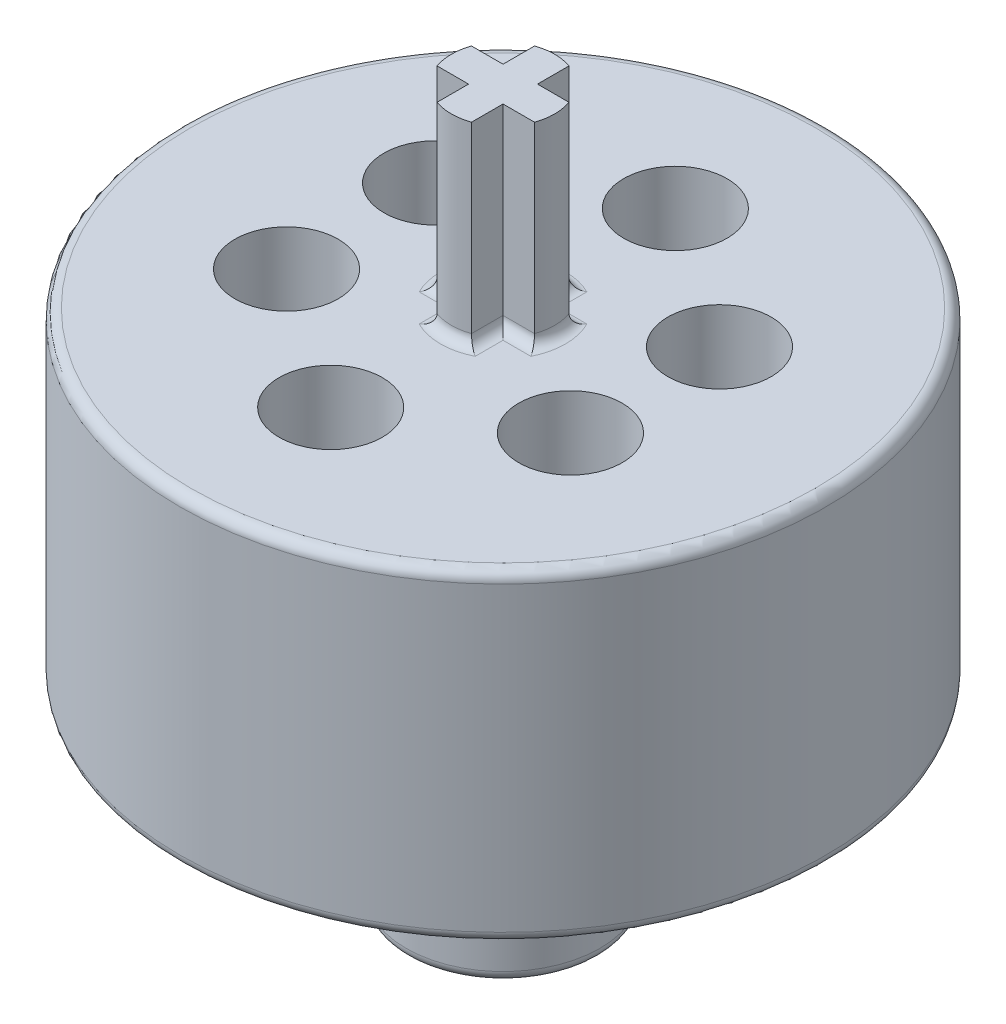
SolidWorks part; units mm, degrees
ref_plane "Plano frontal" through (0, 0, 0) normal (0, 0, 1) x (1, 0, 0)
ref_plane "Plano superior" through (0, 0, 0) normal (0, 1, 0) x (1, 0, 0)
ref_plane "Plano direito" through (0, 0, 0) normal (1, 0, 0) x (0, 0, -1)
sketch "Esboço1" plane through (0, 0, 0) normal (0, 1, 0) x (1, 0, 0)
  circle A4 centre (-6.59, 3.46) radius 2.4
  circle A5 centre (6.59, 3.46) radius 2.4
  circle A6 centre (6.59, -3.46) radius 2.4
  circle A7 centre (0, 8) radius 2.4
  circle A8 centre (0, -8) radius 2.4
  circle A9 centre (-6.59, -3.46) radius 2.4
  point P29 (0, 0)
  point P30 (0, 0)
  point P31 (0, 0)
  point P32 (0, 0)
  point P33 (0, 0)
sketch "Esboço2" plane through (0, 0, 0) normal (0, 1, 0) x (1, 0, 0)
  circle A0 centre (0, 0) radius 15
extrude "Ressalto-extrusão3" add sketch "Esboço2" along normal blind 15
extrude "Corte-extrusão4" cut sketch "Esboço1" along normal blind 15 contours A6 | A5 | A7 | A4 | A8 | A9
sketch "Esboço3" plane through (0, 15, 0) normal (0, 1, 0) x (1, 0, 0)
  line L2 (0.8, 0.8) -> (0.8, 2.2627)
  line L3 (-0.8, 0.8) -> (-0.8, 2.2627)
  line L4 (-0.8, 2.2627) -> (-0.8, 0.8)
  line L5 (0.8, -0.8) -> (0.8, -2.2627)
  line L8 (0.8, 0.8) -> (2.2627, 0.8)
  line L9 (2.2627, 0.8) -> (0.8, 0.8)
  line L10 (0.8, -0.8) -> (2.2627, -0.8)
  line L11 (2.2627, -0.8) -> (0.8, -0.8)
  line L12 (-0.8, -0.8) -> (-2.2627, -0.8)
  line L13 (-0.8, 0.8) -> (-2.2627, 0.8)
  line L14 (-0.8, -0.8) -> (-0.8, -2.2627)
  arc A0 (0.8, 2.2627) -> (-0.8, 2.2627) centre (0, 0) ccw
  arc A1 (-2.2627, 0.8) -> (-2.2627, -0.8) centre (0, 0) ccw
  arc A2 (-0.8, -2.2627) -> (0.8, -2.2627) centre (0, 0) ccw
  arc A3 (2.2627, -0.8) -> (2.2627, 0.8) centre (0, 0) ccw
extrude "Ressalto-extrusão4" add sketch "Esboço3" along normal blind 9 contours L10 A3 L8 L2 A0 L3 L13 A1 L12 L14 A2 L5
sketch "Esboço5" plane through (0, 0, 0) normal (0, -1, 0) x (1, 0, 0)
  circle A0 centre (0, 0) radius 4.5
extrude "Ressalto-extrusão5" add sketch "Esboço5" along normal blind 9
sketch "Esboço6" plane through (0, -9, 0) normal (0, -1, 0) x (1, 0, 0)
  line L0 (1.8785, -0.6865) -> (0.916, 1.7779)
  arc A0 (0.916, 1.7779) -> (1.8785, -0.6865) centre (0, 0) ccw
  dimension "D1" = 1.5
extrude "Corte-extrusão7" cut sketch "Esboço6" against normal blind 7.5
fillet "Filete3" radius 0.5 16 edges at (-0.8, 15, 1.5314) (-1.5314, 15, 0.8) (-2.4, 15, 0) (-1.5314, 15, -0.8) (-0.8, 15, -1.5314) (0, 15, -2.4) (0.8, 15, -1.5314) (1.5314, 15, -0.8) (2.4, 15, 0) (1.5314, 15, 0.8) (0.8, 15, 1.5314) (0, 15, 2.4) (0, -9, -4.5) (0, 0, 4.5) (0, 0, 15) (0, 15, 15)
